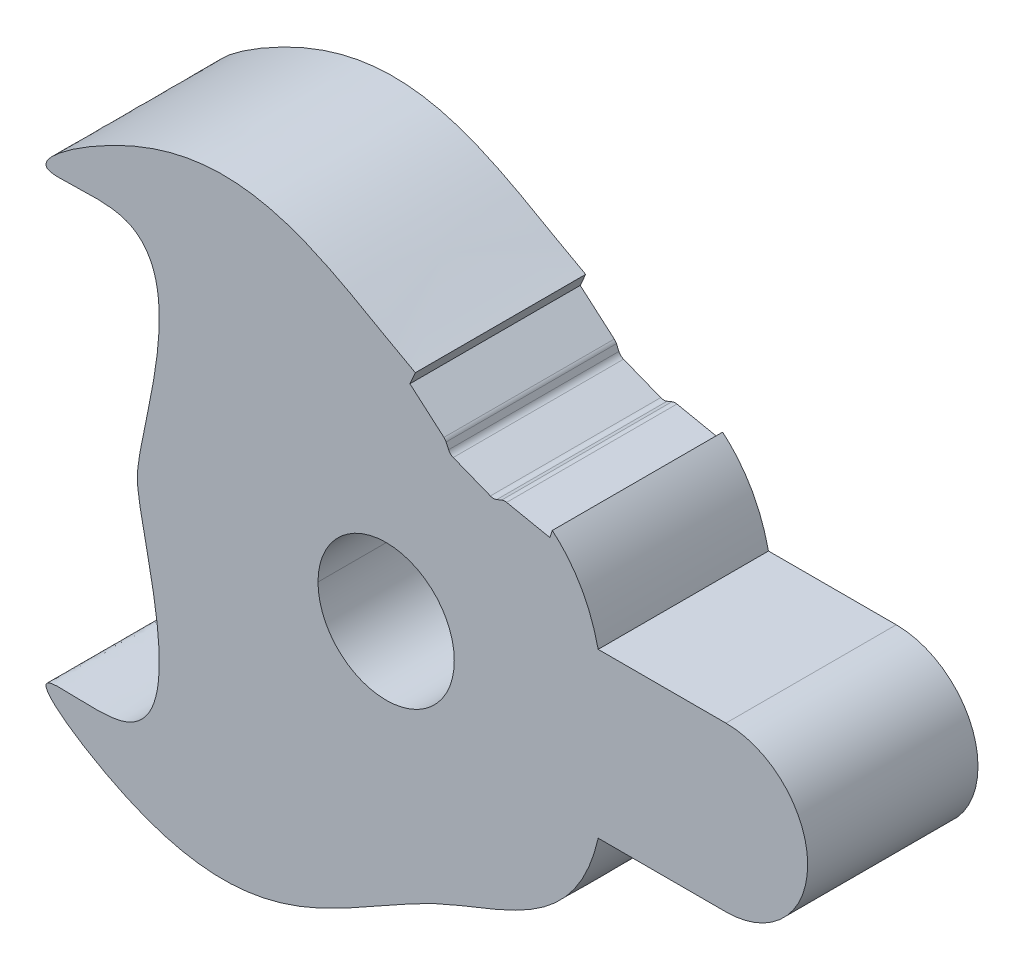
SolidWorks part; units mm, degrees
ref_plane "Front Plane" through (0, 0, 0) normal (0, 0, 1) x (1, 0, 0)
ref_plane "Top Plane" through (0, 0, 0) normal (0, 1, 0) x (1, 0, 0)
ref_plane "Right Plane" through (0, 0, 0) normal (1, 0, 0) x (0, 0, -1)
sketch "Sketch1" plane through (0, 0, 0) normal (0, 0, 1) x (1, 0, 0)
  line L2 (42.41, 9.6) -> (57.41, 9.6)
  line L6 (9.51, 0) -> (-11.6928, 0)
  line L7 (67.01, 0) -> (25.51, 0)
  arc A1 (67.01, 0) -> (57.41, 9.6) centre (57.41, 0) ccw
  arc A2 (9.51, 0) -> (25.51, 0) centre (17.51, 0.02) cw
  spline S0 degree 3 poles (-11.6928, 0) (-11.8393, 4.8945) (-2.3556, 29.35) (-27.8845, 24.1434) (0.6228, 43.5441) (18.6604, 24.2001) (39.8587, 20.776) (42.41, 9.6) knots 0 0 0 0 0.241029 0.319956 0.433187 0.773179 1 1 1 1
  dimension "D2" = 8
  dimension "D3" = 9.51
  dimension "D5" = 25.6795
  dimension "D6" = 26.1273
  dimension "D12" = 9.9764
  dimension "D20" = 23.1433
  dimension "D9" = 16.9
  dimension "D10" = 9.6
  dimension "D22" = 17.51
  dimension "D4" = 9.8579
  dimension "D7" = 33.441
  dimension "D8" = 41.5
  dimension "D11" = 22.2157
  dimension "D13" = 11.6928
  dimension "D14" = 25.55
  dimension "D15" = 23.93
  dimension "D16" = 9.6
  dimension "D17" = 2.25
  dimension "D18" = 1.63
  dimension "D19" = 21.7999
extrude "Boss-Extrude1" add sketch "Sketch1" along normal mid plane 20
mirror "Mirror1" about plane through (67.01, 0, 10) normal (0, 1, 0) of "Boss-Extrude1"
sketch "Sketch2" plane through (0, 0, 10) normal (0, 0, 1) x (1, 0, 0)
  line L12 (37.6, 20.83) -> (36.7457, 18.13)
  line L13 (36.7457, 18.13) -> (31.3572, 19.232)
  line L15 (30.1274, 18.724) -> (25.0122, 20.745)
  line L16 (25.0122, 20.745) -> (24.4616, 21.9563)
  line L17 (24.4616, 21.9563) -> (20.3012, 25.5536)
  line L18 (20.3012, 25.5536) -> (20.94, 26.9987)
  line L19 (37.6, 20.83) -> (20.94, 26.9987)
  line L20 (31.3572, 19.232) -> (30.1274, 18.724)
  spline S2 degree 3 poles (42.41, 9.6) (39.8587, 20.776) (18.6604, 24.2001) (0.6228, 43.5441) (-27.8845, 24.1434) (-2.3556, 29.35) (-11.8393, 4.8945) (-11.6928, 0) knots 0 0 0 0 0.226821 0.566813 0.680044 0.758971 1 1 1 1 construction
  dimension "D1" = 107
  dimension "D2" = 84
  dimension "D3" = 5.5
  dimension "D4" = 136
  dimension "D5" = 136
  dimension "D6" = 1.58
  dimension "D7" = 2.7
  dimension "D8" = 18.13
  dimension "D9" = 16.66
  dimension "D10" = 204.71
  dimension "D11" = 214
  dimension "D12" = 36.7457
extrude "Cut-Extrude1" cut sketch "Sketch2" against normal through all
fillet "Fillet1" radius 1 4 edges at (31.3572, 19.232, 0) (30.1274, 18.724, 0) (25.0122, 20.745, 0) (24.4616, 21.9563, 0)
